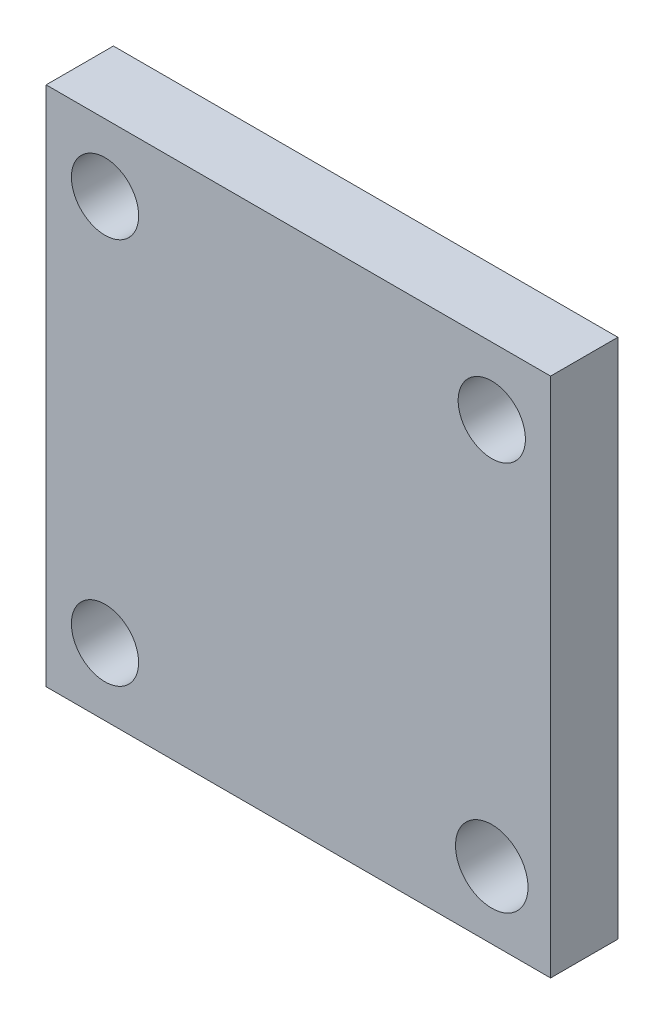
SolidWorks part; units mm, degrees
material "PET"
ref_plane "Front" through (0, 0, 0) normal (0, 0, 1) x (1, 0, 0)
ref_plane "Top" through (0, 0, 0) normal (0, 1, 0) x (1, 0, 0)
ref_plane "Right" through (0, 0, 0) normal (1, 0, 0) x (0, 0, -1)
ref_plane "Plane1" through (0, 0, 0) normal (0, 0, -1) x (-1, 0, 0)
sketch "Sketch1" plane through (0, 0, 0) normal (0, 0, -1) x (-1, 0, 0)
  line L0 (-15.0011, -15.5011) -> (15.0011, -15.5011)
  line L1 (15.0011, -15.5011) -> (15.0011, 15.5011)
  line L2 (15.0011, 15.5011) -> (-15.0011, 15.5011)
  line L3 (-15.0011, 15.5011) -> (-15.0011, -15.5011)
  circle A0 centre (-11.5011, -11.5011) radius 2.1563
  circle A1 centre (11.5011, -11.4989) radius 2
  circle A2 centre (-11.5033, 11.5011) radius 2
  circle A3 centre (11.4989, 11.5033) radius 2
extrude "Boss-Extrude1" add sketch "Sketch1" against normal blind 4
